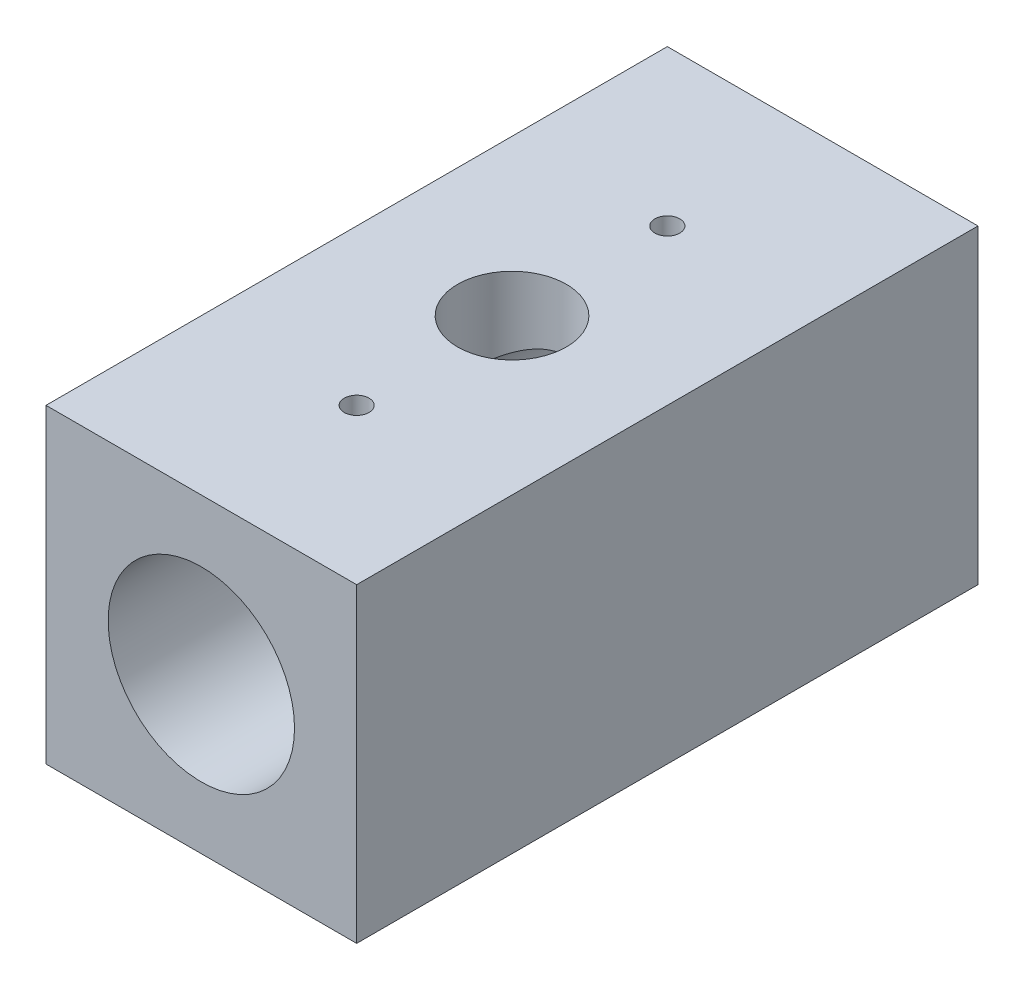
SolidWorks part; units mm, degrees
ref_plane "Ebene vorne" through (0, 0, 0) normal (0, 0, 1) x (1, 0, 0)
ref_plane "Ebene oben" through (0, 0, 0) normal (0, 1, 0) x (1, 0, 0)
ref_plane "Ebene rechts" through (0, 0, 0) normal (1, 0, 0) x (0, 0, -1)
sketch "Skizze1" plane through (0, 0, 0) normal (0, 0, 1) x (1, 0, 0)
  line L1 (-10, -10) -> (10, -10)
  line L2 (-10, -10) -> (-10, 10)
  line L3 (-10, 10) -> (10, 10)
  line L4 (10, -10) -> (10, 10)
  line L5 (-10, -10) -> (10, 10) construction
  line L6 (-10, 10) -> (10, -10) construction
  circle A0 centre (0, 0) radius 6
  point P0 (0, 0)
  dimension "D3" = 12
  dimension "D1" = 20
  dimension "D2" = 20
extrude "Aufsatz-Linear austragen1" add sketch "Skizze1" along normal blind 40
sketch "Skizze2" plane through (0, -10, 0) normal (0, -1, 0) x (1, 0, 0)
  line L0 (-10, 0) -> (10, 0) construction
  line L1 (-10, 40) -> (10, 40) construction
  circle A0 centre (0, 30) radius 1
  circle A1 centre (0, 10) radius 1
  circle A2 centre (0, 20) radius 1.75
  dimension "D1" = 2
  dimension "D2" = 2
  dimension "D5" = 3.5
  dimension "D3" = 10
  dimension "D4" = 20
  dimension "D6" = 20
extrude "Schnitt-Linear austragen1" cut sketch "Skizze2" against normal blind 3
sketch "Skizze3" plane through (0, -7, 0) normal (0, -1, 0) x (1, 0, 0)
  circle A0 centre (0, 30) radius 0.5
  circle A1 centre (0, 10) radius 0.5
  dimension "D1" = 1
  dimension "D2" = 1
extrude "Schnitt-Linear austragen2" cut sketch "Skizze3" against normal blind 2
ref_plane "Ebene1" through (0, -8, 0) normal (0, -1, 0) x (-1, 0, 0)
sketch "Skizze4" plane through (0, -8, 0) normal (0, -1, 0) x (-1, 0, 0)
  line L0 (-10, 0) -> (10, 0) construction
  line L1 (-10, -40) -> (-10, 0) construction
  circle A0 centre (0, -20) radius 3.25
  dimension "D1" = 6.5
  dimension "D2" = 20
  dimension "D3" = 10
extrude "Schnitt-Linear austragen3" cut sketch "Skizze4" against normal up to next
hole_wizard "Ø7.0 (7) Durchmesser Bohrung1" positions "3D-Skizze2" profile "Skizze8" hole size "Ø7.0" standard "ISO"
sketch3d "3D-Skizze2"
  line L0 (10, 10, 40) -> (10, 10, 0) construction
  line L1 (10, 10, 0) -> (-10, 10, 0) construction
  point P0 (0, 10, 20)
  dimension "D1" = 10
  dimension "D2" = 20
sketch "Skizze8" plane through (0, 10, 20) normal (1, 0, 0) x (0, 0, 1)
  line L0 (0, 0) -> (0, 4)
  line L1 (0, 4) -> (3.5, 4)
  line L2 (3.5, 4) -> (3.5, 0)
  line L5 (3.5, 0) -> (0, 0)
  line L11 (0, -6.35) -> (0, 107.95) construction
  dimension "Bohrerdurchmesser" = 7
  dimension "Bohrungstiefe" = 4
hole_wizard "M2 Gewindebohrung1" positions "3D-Skizze3" profile "Skizze9" tap size "M2" standard "ISO"
sketch3d "3D-Skizze3"
  line L0 (10, 10, 40) -> (10, 10, 0) construction
  line L1 (10, 10, 40) -> (-10, 10, 40) construction
  point P0 (0, 10, 30)
  point P2 (0, 10, 10)
  dimension "D1" = 10
  dimension "D2" = 20
  dimension "D3" = 10
  dimension "D4" = 10
sketch "Skizze9" plane through (0, 10, 30) normal (1, 0, 0) x (0, 0, 1)
  line L0 (0, 0) -> (0, 4)
  line L1 (0, 4) -> (0.8, 4)
  line L2 (0.8, 4) -> (0.8, 0)
  line L5 (0.8, 0) -> (0, 0)
  line L11 (0, -6.35) -> (0, 107.95) construction
  dimension "Bohrerdurchmesser" = 1.6
  dimension "Bohrungstiefe" = 4
cosmetic thread "Bohrungsgewinde1" parameters "D2"=2
cosmetic thread "Bohrungsgewinde2" parameters "D2"=2
